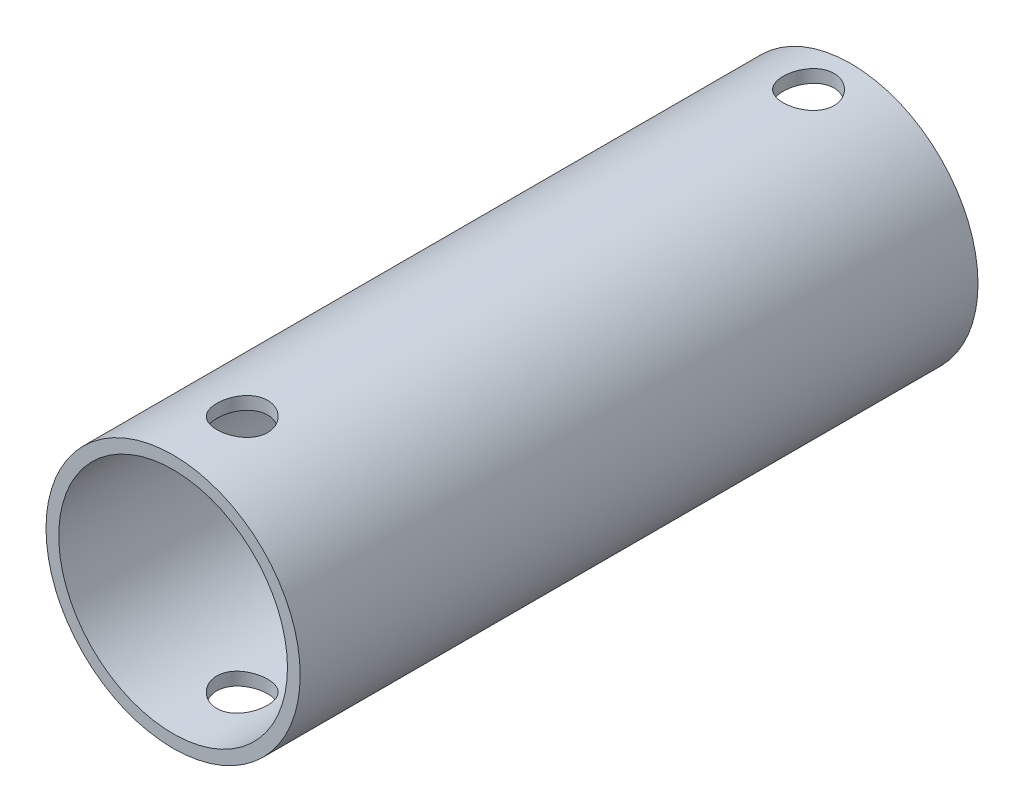
SolidWorks part; units mm, degrees
ref_plane "Front Plane" through (0, 0, 0) normal (0, 0, 1) x (1, 0, 0)
ref_plane "Top Plane" through (0, 0, 0) normal (0, 1, 0) x (1, 0, 0)
ref_plane "Right Plane" through (0, 0, 0) normal (1, 0, 0) x (0, 0, -1)
sketch "Sketch1" plane through (0, 0, 0) normal (0, 0, 1) x (1, 0, 0)
  circle A0 centre (0, 0) radius 15
  circle A1 centre (0, 0) radius 13.5
  dimension "D1" = 30
  dimension "D2" = 1.5
extrude "Boss-Extrude1" add sketch "Sketch1" along normal blind 80
sketch "Sketch2" plane through (0, 0, 0) normal (0, 1, 0) x (1, 0, 0)
  circle A0 centre (0, -5) radius 3
  dimension "D2" = 6
  dimension "D1" = 5
extrude "Cut-Extrude1" cut sketch "Sketch2" against normal mid plane 66 contours A0
sketch "Sketch3" plane through (0, 0, 0) normal (0, -1, 0) x (1, 0, 0)
  circle A0 centre (0, 71.8396) radius 3
  dimension "D2" = 6
extrude "Cut-Extrude2" cut sketch "Sketch3" against normal mid plane 66
